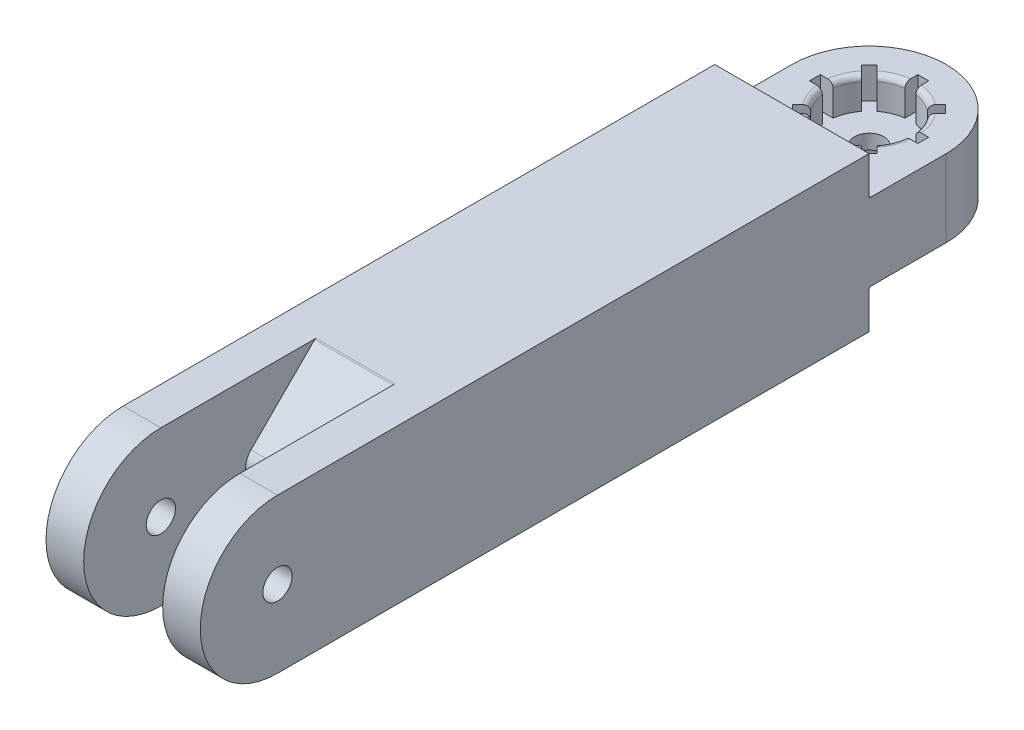
SolidWorks part; units mm, degrees
ref_plane "Front Plane" through (0, 0, 0) normal (0, 0, 1) x (1, 0, 0)
ref_plane "Top Plane" through (0, 0, 0) normal (0, 1, 0) x (1, 0, 0)
ref_plane "Right Plane" through (0, 0, 0) normal (1, 0, 0) x (0, 0, -1)
sketch "Sketch1" plane through (0, 0, 0) normal (0, 0, 1) x (1, 0, 0)
  line L1 (-21, 21) -> (21, 21)
  line L2 (-21, 21) -> (-21, -21)
  line L3 (-21, -21) -> (21, -21)
  line L4 (21, 21) -> (21, -21)
  line L5 (-21, 21) -> (21, -21) construction
  line L6 (-21, -21) -> (21, 21) construction
  point P0 (0, 0)
  dimension "D1" = 42
  dimension "D2" = 42
extrude "Boss-Extrude1" add sketch "Sketch1" along normal blind 140
ref_plane "Plane1" through (0, 0, 140) normal (0, 0, 1) x (1, 0, 0)
sketch "Sketch2" plane through (0, 0, 140) normal (0, 0, 1) x (1, 0, 0)
  line L0 (-21, -21) -> (21, -21) construction
  line L1 (-21, 21) -> (-10.75, 21)
  line L2 (-21, 21) -> (-21, -21)
  line L3 (-21, -21) -> (-10.75, -21)
  line L4 (-10.75, 21) -> (-10.75, -21)
  line L5 (21, 21) -> (-21, 21) construction
  line L6 (21, -21) -> (10.75, -21)
  line L7 (21, -21) -> (21, 21)
  line L8 (21, 21) -> (10.75, 21)
  line L9 (10.75, -21) -> (10.75, 21)
  dimension "D1" = 10.25
  dimension "D2" = 10.25
extrude "Boss-Extrude2" add sketch "Sketch2" along normal blind 21
ref_plane "Plane2" through (-10.75, 0, 0) normal (1, 0, 0) x (0, 0, -1)
sketch "Sketch3" plane through (-10.75, 0, 0) normal (1, 0, 0) x (0, 0, -1)
  line L0 (-161, -21) -> (-161, 21)
  arc A0 (-161, -21) -> (-161, 21) centre (-161, 0) cw
  dimension "D1" = 21
ref_plane "Plane3" through (0, -21, 0) normal (0, -1, 0) x (-1, 0, 0)
ref_plane "Plane4" through (10.75, 0, 0) normal (-1, 0, 0) x (0, 0, 1)
sketch "Sketch5" plane through (10.75, 0, 0) normal (-1, 0, 0) x (0, 0, 1)
  line L0 (161, 21) -> (161, -21)
  line L4 (140, 21) -> (140, -21)
  line L5 (140, -21) -> (161, -21)
  line L6 (161, -21) -> (161, 21)
  line L7 (161, 21) -> (140, 21)
  line L8 (140, 21) -> (140, -21)
  line L9 (140, -21) -> (161, -21)
  line L11 (161, 21) -> (140, 21)
  arc A0 (161, 21) -> (161, -21) centre (161, 0) cw
  dimension "D1" = 21
  dimension "D2" = 0
extrude "Boss-Extrude4" add sketch "Sketch5" against normal blind 10.25 contours A0 L0
extrude "Boss-Extrude5" add sketch "Sketch3" against normal blind 10.25
sketch "Sketch6" plane through (10.75, 0, 0) normal (-1, 0, 0) x (0, 0, 1)
  line L0 (161, -21) -> (161, 21) construction
  circle A0 centre (161, 0) radius 3.975
  dimension "D1" = 7.95
extrude "Cut-Extrude1" cut sketch "Sketch6" against normal through all
ref_plane "Plane5" through (-10.75, 0, 0) normal (1, 0, 0) x (0, 0, -1)
sketch "Sketch8" plane through (-10.75, 0, 0) normal (1, 0, 0) x (0, 0, -1)
  line L0 (-161, -21) -> (-161, 21) construction
  circle A0 centre (-161, 0) radius 3.975
  dimension "D1" = 7.95
extrude "Cut-Extrude2" cut sketch "Sketch8" against normal through all
ref_plane "Plane6" through (0, 0, 0) normal (0, 0, -1) x (-1, 0, 0)
sketch "Sketch9" plane through (0, 0, 0) normal (0, 0, -1) x (-1, 0, 0)
  line L0 (21, 21) -> (21, -21) construction
  line L1 (21, 10.5) -> (-21, 10.5)
  line L2 (21, 10.5) -> (21, -10.5)
  line L3 (21, -10.5) -> (-21, -10.5)
  line L4 (-21, 10.5) -> (-21, -10.5)
  line L5 (-21, -21) -> (-21, 21) construction
  line L6 (-21, 21) -> (21, 21) construction
  line L7 (21, -21) -> (-21, -21) construction
  point P8 (21, 7.0191)
  dimension "D1" = 10.5
  dimension "D2" = 10.5
extrude "Boss-Extrude6" add sketch "Sketch9" along normal blind 21
ref_plane "Plane7" through (0, -10.5, 0) normal (0, -1, 0) x (-1, 0, 0)
sketch "Sketch10" plane through (0, -10.5, 0) normal (0, -1, 0) x (-1, 0, 0)
  line L0 (-21, 21) -> (21, 21)
  arc A0 (-21, 21) -> (21, 21) centre (0, 21) cw
  dimension "D1" = 21
extrude "Boss-Extrude7" add sketch "Sketch10" against normal blind 21
sketch "Sketch11" plane through (0, -10.5, 0) normal (0, -1, 0) x (-1, 0, 0)
  line L0 (21, 21) -> (-21, 21) construction
  circle A0 centre (0, 21) radius 11.35
  dimension "D1" = 22.7
extrude "Cut-Extrude3" cut sketch "Sketch11" against normal blind 8.5
ref_plane "Plane8" through (10.75, 0, 0) normal (-1, 0, 0) x (0, 0, 1)
sketch "Sketch16" plane through (10.75, 0, 0) normal (-1, 0, 0) x (0, 0, 1)
  line L0 (140, 21) -> (140, 0)
  line L1 (140, 21) -> (140, -21) construction
  line L2 (140, 0) -> (140, -21)
  line L3 (140, -21) -> (119, -21)
  line L4 (119, -21) -> (140, 0)
  line L5 (140, 21) -> (119, 21)
  line L6 (119, 21) -> (140, 0)
  line L7 (161, 0) -> (140, 0) construction
  dimension "D1" = 21
  dimension "D2" = 21
extrude "Cut-Extrude4" cut sketch "Sketch16" along normal blind 21.5 contours L0 L5 L6 | L2 L3 L4
fillet "Fillet1" radius 5 1 edges at (0, 0, 140)
ref_plane "Plane9" through (0, -10.5, 0) normal (0, -1, 0) x (-1, 0, 0)
ref_plane "Plane10" through (0, 10.5, 0) normal (0, 1, 0) x (1, 0, 0)
sketch "Sketch18" plane through (0, 10.5, 0) normal (0, 1, 0) x (1, 0, 0)
  line L0 (21, 21) -> (-21, 21) construction
  circle A0 centre (0, 21) radius 11.35
  dimension "D1" = 22.7
extrude "Cut-Extrude5" cut sketch "Sketch18" against normal blind 8.5
sketch "Sketch19" plane through (0, -2, 0) normal (0, -1, 0) x (1, 0, 0)
  circle A0 centre (0, -21) radius 3.975
  dimension "D1" = 7.95
extrude "Cut-Extrude6" cut sketch "Sketch19" against normal blind 8.5
fillet "Fillet4" radius 1.5 1 edges at (11.35, -10.5, -21)
fillet "Fillet5" radius 1.5 1 edges at (-11.35, 10.5, -21)
sketch "Sketch20" plane through (0, 10.5, 0) normal (0, 1, 0) x (1, 0, 0)
  line L1 (-1.48, 35.755) -> (1.48, 35.755)
  line L2 (-1.48, 35.755) -> (-1.48, 31.945)
  line L3 (-1.48, 31.945) -> (1.48, 31.945)
  line L4 (1.48, 35.755) -> (1.48, 31.945)
  line L5 (-1.48, 35.755) -> (1.48, 31.945) construction
  line L6 (-1.48, 31.945) -> (1.48, 35.755) construction
  circle A0 centre (0, 21) radius 12.85 construction
  point P0 (0, 33.85)
  dimension "D1" = 2.96
  dimension "D2" = 3.81
extrude "Cut-Extrude7" cut sketch "Sketch20" against normal blind 8.5
pattern_circular "CirPattern1" count 8 over 360 about axis through (0, 0, -21) along (0, 1, 0) of "Cut-Extrude7"
ref_plane "Plane11" through (0, 0, 0) normal (0, 1, 0) x (1, 0, 0)
sketch "Sketch21" plane through (0, 0, 0) normal (0, 1, 0) x (1, 0, 0)
  line L0 (0, 43.1461) -> (0, -8.8095) construction
mirror "Mirror1" about plane through (0, 0, 0) normal (0, 1, 0) of "CirPattern1", "Cut-Extrude7"
fillet "Fillet6" radius 0.5 1 edges at (0, -10.5, 0)
fillet "Fillet7" radius 0.5 1 edges at (0, 10.5, 0)
fillet "Fillet8" radius 0.5 1 edges at (0, -21, 119)
fillet "Fillet9" radius 0.5 1 edges at (0, 21, 119)
